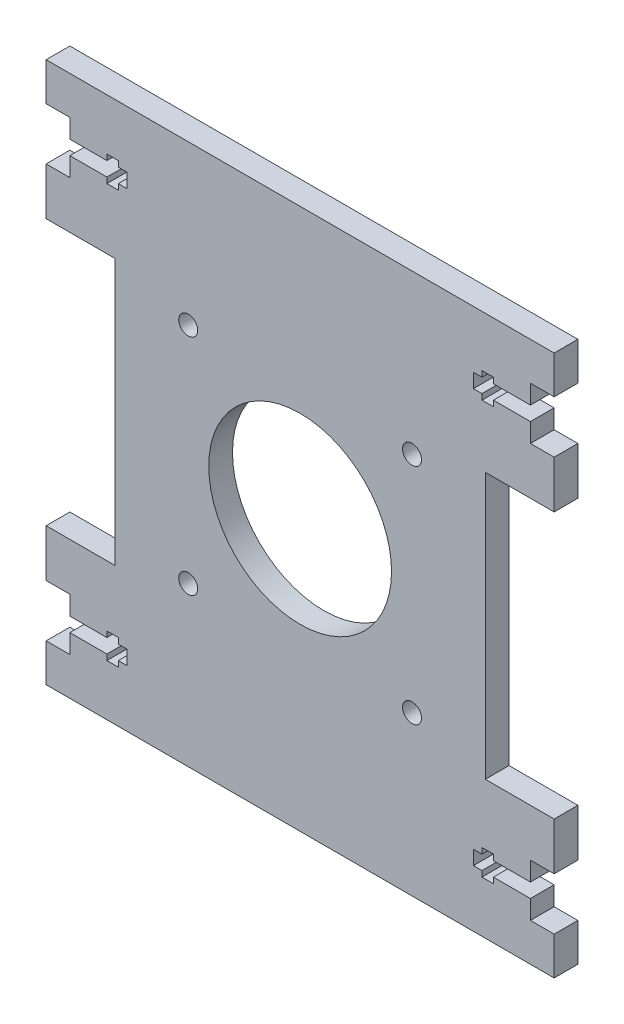
SolidWorks part; units mm, degrees
ref_plane "Plano frontal" through (0, 0, 0) normal (0, 0, 1) x (1, 0, 0)
ref_plane "Plano superior" through (0, 0, 0) normal (0, 1, 0) x (1, 0, 0)
ref_plane "Plano direito" through (0, 0, 0) normal (1, 0, 0) x (0, 0, -1)
sketch "Model" plane through (0, 0, 0) normal (0, 0, 1) x (1, 0, 0)
  line L0 (-87.4999, 136.9999) -> (-79.7, 136.9999)
  line L1 (-79.7, 136.9999) -> (-79.7, 135.7999)
  line L2 (-79.7, 135.7999) -> (-77.3, 135.7999)
  line L3 (-77.3, 135.7999) -> (-77.3, 136.9999)
  line L4 (-77.3, 136.9999) -> (-75.5, 136.9999)
  line L5 (-75.5, 136.9999) -> (-75.5, 139.9999)
  line L6 (-75.5, 139.9999) -> (-77.3, 139.9999)
  line L7 (-77.3, 139.9999) -> (-77.3, 141.1999)
  line L8 (-77.3, 141.1999) -> (-79.7, 141.1999)
  line L9 (-79.7, 141.1999) -> (-79.7, 139.9999)
  line L10 (-79.7, 139.9999) -> (-87.4999, 139.9999)
  line L11 (-87.4999, 139.9999) -> (-87.4999, 143.9715)
  line L12 (-87.4999, 143.9715) -> (-92.4999, 143.9715)
  line L13 (-92.4999, 143.9715) -> (-92.4999, 151.9999)
  line L14 (-92.4999, 151.9999) -> (14.5001, 151.9999)
  line L15 (14.5001, 151.9999) -> (14.5001, 143.9999)
  line L16 (14.5001, 143.9999) -> (9.5001, 143.9999)
  line L17 (9.5001, 143.9999) -> (9.5001, 139.9999)
  line L18 (9.5001, 139.9999) -> (1.7, 139.9999)
  line L19 (1.7, 139.9999) -> (1.7, 141.1999)
  line L20 (1.7, 141.1999) -> (-0.7, 141.1999)
  line L21 (-0.7, 141.1999) -> (-0.7, 139.9999)
  line L22 (-0.7, 139.9999) -> (-2.5, 139.9999)
  line L23 (-2.5, 139.9999) -> (-2.5, 136.9999)
  line L24 (-2.5, 136.9999) -> (-0.7, 136.9999)
  line L25 (-0.7, 136.9999) -> (-0.7, 135.7999)
  line L26 (-0.7, 135.7999) -> (1.7, 135.7999)
  line L27 (1.7, 135.7999) -> (1.7, 136.9999)
  line L28 (1.7, 136.9999) -> (9.5001, 136.9999)
  line L29 (9.5001, 136.9999) -> (9.5001, 133)
  line L30 (9.5001, 133) -> (14.5001, 133)
  line L31 (14.5001, 133) -> (14.5001, 123)
  line L32 (14.5001, 123) -> (0, 123)
  line L33 (0, 123) -> (0, 66.9999)
  line L34 (0, 66.9999) -> (14.5001, 66.9999)
  line L35 (14.5001, 66.9999) -> (14.5001, 56.9999)
  line L36 (14.5001, 56.9999) -> (9.5001, 56.9999)
  line L37 (9.5001, 56.9999) -> (9.5001, 53)
  line L38 (9.5001, 53) -> (1.7, 53)
  line L39 (1.7, 53) -> (1.7, 54.2)
  line L40 (1.7, 54.2) -> (-0.7, 54.2)
  line L41 (-0.7, 54.2) -> (-0.7, 53)
  line L42 (-0.7, 53) -> (-2.5, 53)
  line L43 (-2.5, 53) -> (-2.5, 50)
  line L44 (-2.5, 50) -> (-0.7, 50)
  line L45 (-0.7, 50) -> (-0.7, 48.7999)
  line L46 (-0.7, 48.7999) -> (1.7, 48.7999)
  line L47 (1.7, 48.7999) -> (1.7, 50)
  line L48 (1.7, 50) -> (9.5001, 50)
  line L49 (9.5001, 50) -> (9.5001, 46)
  line L50 (9.5001, 46) -> (14.5001, 46)
  line L51 (14.5001, 46) -> (14.5001, 38)
  line L52 (14.5001, 38) -> (-92.4999, 38)
  line L53 (-92.4999, 38) -> (-92.4999, 46)
  line L54 (-92.4999, 46) -> (-87.4999, 46)
  line L55 (-87.4999, 46) -> (-87.4999, 49.9999)
  line L56 (-87.4999, 49.9999) -> (-79.7, 49.9999)
  line L57 (-79.7, 49.9999) -> (-79.7, 48.7999)
  line L58 (-79.7, 48.7999) -> (-77.3, 48.7999)
  line L59 (-77.3, 48.7999) -> (-77.3, 49.9999)
  line L60 (-77.3, 49.9999) -> (-75.5, 49.9999)
  line L61 (-75.5, 49.9999) -> (-75.5, 53)
  line L62 (-75.5, 53) -> (-77.3, 53)
  line L63 (-77.3, 53) -> (-77.3, 54.2)
  line L64 (-77.3, 54.2) -> (-79.7, 54.2)
  line L65 (-79.7, 54.2) -> (-79.7, 53)
  line L66 (-79.7, 53) -> (-87.4999, 53)
  line L67 (-87.4999, 53) -> (-87.4999, 56.9999)
  line L68 (-87.4999, 56.9999) -> (-92.5004, 56.9999)
  line L69 (-92.5004, 56.9999) -> (-92.5004, 66.9999)
  line L70 (-92.5004, 66.9999) -> (-78, 66.9999)
  line L71 (-78, 66.9999) -> (-78, 123)
  line L72 (-78, 123) -> (-92.4999, 123)
  line L73 (-92.4999, 123) -> (-92.4999, 133)
  line L74 (-92.4999, 133) -> (-87.4999, 133)
  line L75 (-87.4999, 133) -> (-87.4999, 136.9999)
  circle A0 centre (-62.5699, 118.57) radius 2
  circle A1 centre (-15.4299, 118.57) radius 2
  circle A2 centre (-62.5699, 71.43) radius 2
  circle A3 centre (-15.4299, 71.43) radius 2
  circle A4 centre (-38.9999, 95) radius 19.25
extrude "Ressalto-extrusão1" add sketch "Model" along normal blind 5
